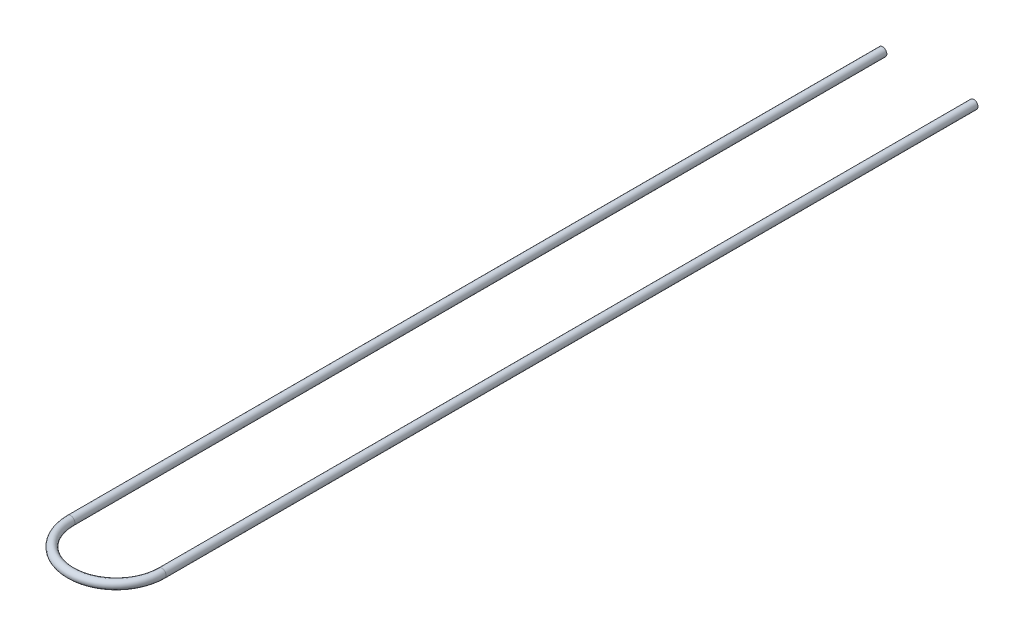
SolidWorks part; units mm, degrees
ref_plane "Front Plane" through (0, 0, 0) normal (0, 0, 1) x (1, 0, 0)
ref_plane "Top Plane" through (0, 0, 0) normal (0, 1, 0) x (1, 0, 0)
ref_plane "Right Plane" through (0, 0, 0) normal (1, 0, 0) x (0, 0, -1)
sketch "Sketch1" plane through (0, 0, 0) normal (0, 1, 0) x (1, 0, 0)
  line L0 (200.31, -300) -> (200.31, -2440)
  line L2 (-40, -300) -> (-40, -2440)
  arc A0 (-40, -2440) -> (200.31, -2440) centre (80.155, -2440) ccw
  dimension "D1" = 2140
  dimension "D2" = 240.31
ref_plane "Plane1" through (200.31, 0, 300) normal (0, 0, -1) x (-1, 0, 0)
sketch "Sketch2" plane through (200.31, 0, 300) normal (0, 0, -1) x (-1, 0, 0)
  circle A0 centre (0, 0) radius 9.95
  circle A1 centre (0, 0) radius 11.1
  dimension "D1" = 22.2
  dimension "D2" = 19.9
sweep "Sweep1" add profiles "Sketch2" path "Sketch1"
